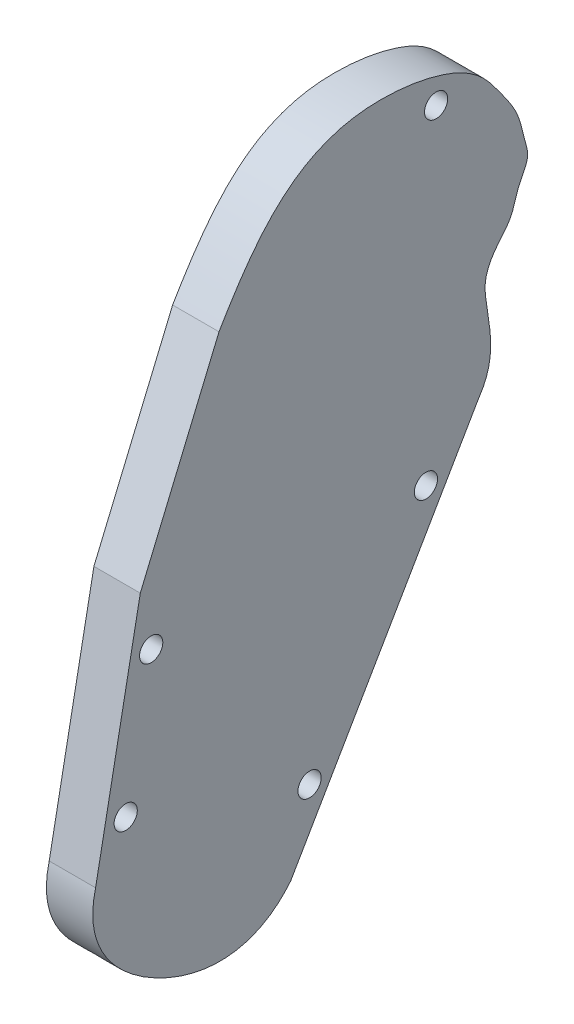
SolidWorks part; units mm, degrees
ref_plane "Front Plane" through (0, 0, 0) normal (0, 0, 1) x (1, 0, 0)
ref_plane "Top Plane" through (0, 0, 0) normal (0, 1, 0) x (1, 0, 0)
ref_plane "Right Plane" through (0, 0, 0) normal (1, 0, 0) x (0, 0, -1)
sketch "Sketch1" plane through (0, 0, 0) normal (1, 0, 0) x (0, 0, -1)
  line L0 (-22.743, -21.8561) -> (-17.9229, 3.2427)
  line L1 (-17.9229, 3.2427) -> (-9.439, 23.3959)
  line L2 (18.5765, 3.2427) -> (-1.7156, -31.7391)
  spline S0 degree 3 poles (-22.743, -21.8561) (-24.1424, -27.3028) (-16.6039, -35.6647) (-5.5981, -36.5145) (-1.7156, -31.7391) knots 0 0 0 0 0.48419 1 1 1 1
  spline S1 degree 3 poles (18.5765, 3.2427) (20.3999, 5.8715) (19.6867, 9.3922) (19.0567, 13.8193) (20.2071, 16.2847) (22.2362, 18.1541) (22.6647, 20.9001) (24.1424, 22.8746) (23.3712, 25.1104) (22.9232, 27.7566) (21.0205, 30.3604) (19.1115, 33.0147) (16.8206, 34.5538) (13.5726, 35.7835) (9.2414, 36.5145) (4.1127, 36.2299) (-3.4789, 33.0863) (-7.1174, 27.3181) (-9.439, 23.3959) knots 0 0 0 0 0.124664 0.161438 0.19566 0.241957 0.280315 0.317452 0.342381 0.380427 0.438288 0.482854 0.526779 0.559206 0.638222 0.721837 0.785952 1 1 1 1
extrude "Boss-Extrude1" add sketch "Sketch1" against normal blind 5
sketch "Sketch2" plane through (53, 0, 0) normal (1, 0, 0) x (0, 0, -1)
  circle A0 centre (-16.7505, -2.583) radius 1.25
  circle A1 centre (-19.496, -16.8792) radius 1.25
  circle A2 centre (0.3228, -23.7409) radius 1.25
  circle A3 centre (12.867, -2.1159) radius 1.25
  circle A4 centre (13.9632, 32.8296) radius 1.25
extrude "Cut-Extrude2" cut sketch "Sketch2" against normal blind 100
